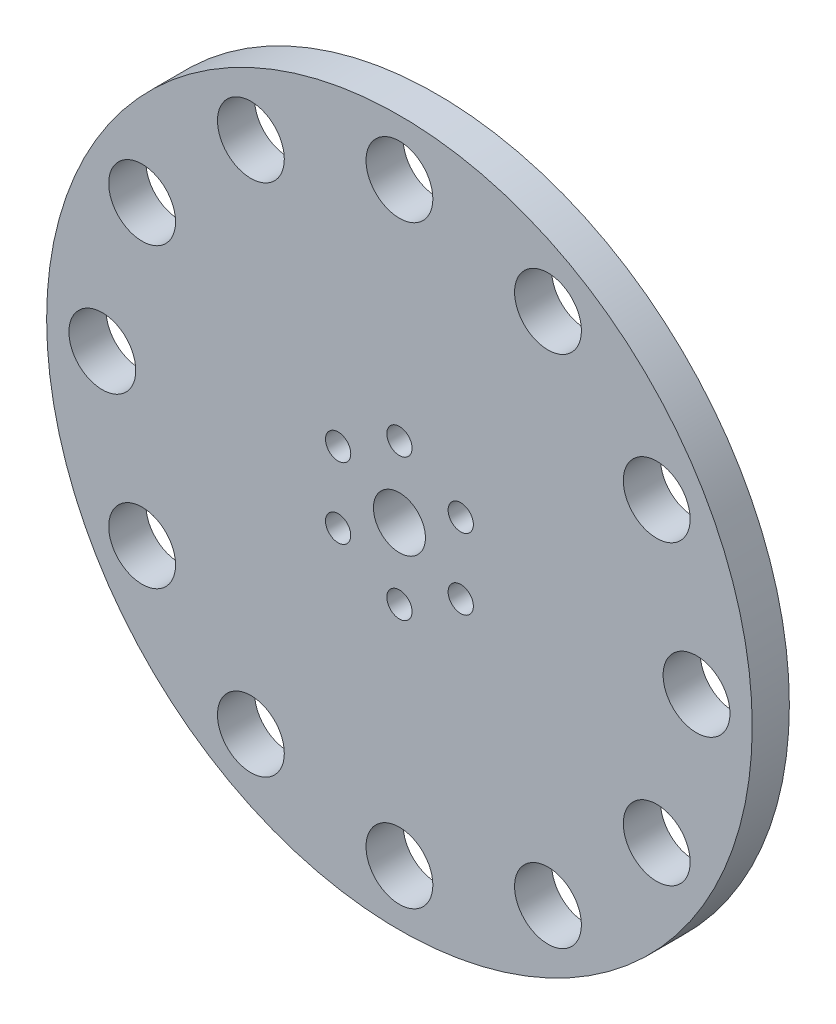
SolidWorks part; units mm, degrees
material "ABS"
ref_plane "Front Plane" through (0, 0, 0) normal (0, 0, 1) x (1, 0, 0)
ref_plane "Top Plane" through (0, 0, 0) normal (0, 1, 0) x (1, 0, 0)
ref_plane "Right Plane" through (0, 0, 0) normal (1, 0, 0) x (0, 0, -1)
sketch "Sketch6" plane through (0, 0, 0) normal (0, 0, 1) x (1, 0, 0)
  circle A0 centre (0, 0) radius 47.5
  circle A1 centre (0, 0) radius 3.5
  dimension "D1" = 95
  dimension "D2" = 7
extrude "Boss-Extrude1" add sketch "Sketch6" along normal blind 5
sketch "Sketch7" plane through (0, 0, 5) normal (0, 0, 1) x (1, 0, 0)
  line L0 (0, 0) -> (0, 9.53) construction
  circle A0 centre (0, 0) radius 9.53 construction
  circle A1 centre (0, 0) radius 40 construction
  circle A2 centre (0, 9.53) radius 1.7
  circle A3 centre (0, 40) radius 4.5
  circle A4 centre (8.2532, 4.765) radius 1.7
  circle A5 centre (8.2532, -4.765) radius 1.7
  circle A6 centre (0, -9.53) radius 1.7
  circle A7 centre (-8.2532, -4.765) radius 1.7
  circle A8 centre (-8.2532, 4.765) radius 1.7
  circle A9 centre (20, 34.641) radius 4.5
  circle A10 centre (34.641, 20) radius 4.5
  circle A11 centre (40, 0) radius 4.5
  circle A12 centre (34.641, -20) radius 4.5
  circle A13 centre (20, -34.641) radius 4.5
  circle A14 centre (0, -40) radius 4.5
  circle A15 centre (-20, -34.641) radius 4.5
  circle A16 centre (-34.641, -20) radius 4.5
  circle A17 centre (-40, 0) radius 4.5
  circle A18 centre (-34.641, 20) radius 4.5
  circle A19 centre (-20, 34.641) radius 4.5
  dimension "D1" = 80
  dimension "D2" = 19.06
  dimension "D3" = 9
  dimension "D4" = 3.4
  dimension "D5" = 6
  dimension "D6" = 12
extrude "Cut-Extrude3" cut sketch "Sketch7" against normal blind 5
